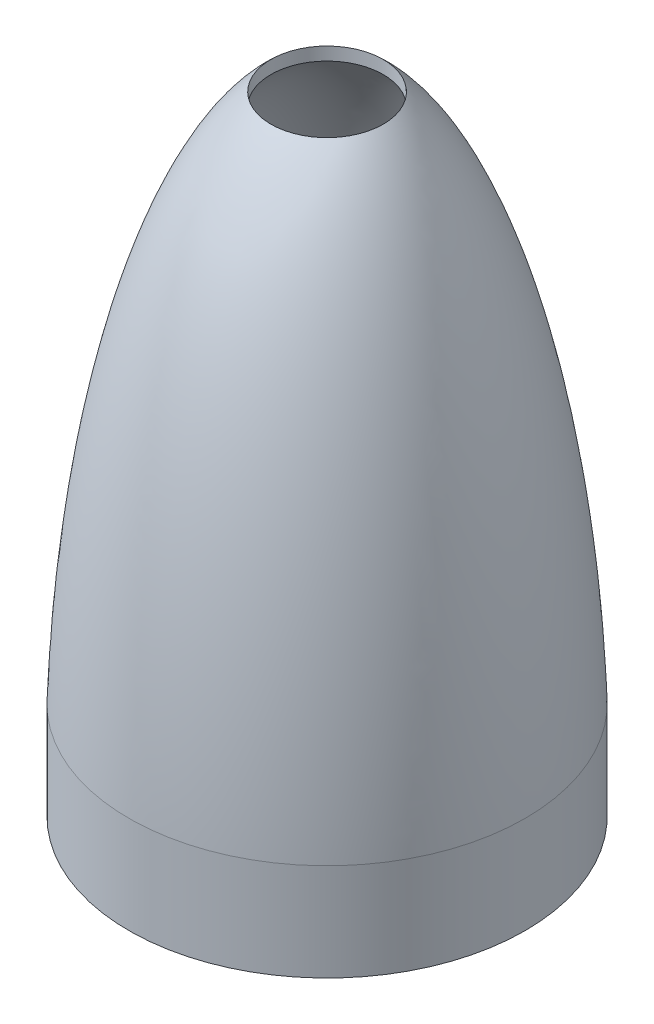
SolidWorks part; units mm, degrees
material "VeroWhite Plus"
ref_plane "Front Plane" through (0, 0, 0) normal (0, 0, 1) x (1, 0, 0)
ref_plane "Top Plane" through (0, 0, 0) normal (0, 1, 0) x (1, 0, 0)
ref_plane "Right Plane" through (0, 0, 0) normal (1, 0, 0) x (0, 0, -1)
sketch "Sketch1" plane through (0, 0, 0) normal (0, 0, 1) x (1, 0, 0)
  line L0 (0, 0) -> (57.6864, 0) construction
  line L1 (0, 19.918) -> (0, 197.9164) construction
  line L2 (0, 19.918) -> (63.5, 19.918) construction
  line L3 (0, 19.918) -> (0, 0) construction
  line L13 (0, 197.9164) -> (0, 194.918)
  line L14 (63.5, 19.918) -> (63.5, -11.258)
  line L15 (63.5, -11.258) -> (60.5, -11.258)
  line L16 (60.5, -11.258) -> (60.5, 19.918)
  ellipse E1 centre (0, 0) end of major axis (0, 197.9164) minor radius 63.824 (63.5, 19.918) -> (0, 197.9164) ccw
  spline S0 degree 1 poles (60.5032, 19.8202) (0, 194.918) knots 0 0 1 1 construction
  spline S1 degree 3 poles (60.5032, 19.8202) (60.5024, 19.8446) (60.5011, 19.8854) (60.4027, 22.885) (60.1628, 28.8505) (59.5081, 40.6956) (58.3579, 55.3596) (56.4637, 72.479) (53.2754, 94.4792) (48.0987, 120.0698) (40.2045, 146.6573) (30.9343, 168.1839) (22.3996, 181.2376) (15.3903, 188.4638) (10.1461, 192.2524) (5.8682, 194.0812) (2.5035, 194.7993) (0.838, 194.918) (0, 194.918) knots -1.469987 -1.469987 -1.469987 -1.469987 -1.469613 -1.469364 -1.42405 -1.378113 -1.286239 -1.194365 -1.10249 -0.918742 -0.734994 -0.551245 -0.367497 -0.275623 -0.183748 -0.091874 -0.045937 0 0 0 0 only from (60.5, 19.918) to (0, 194.918)
  dimension "D1" = 63.5
  dimension "D2" = 31.176
  dimension "D3" = 19.918
  dimension "D4" = 3
  dimension "D5" = 175
revolve "Revolve1" add sketch "Sketch1" angle 360 about L1
ref_plane "Plane1" through (0, -11.258, 0) normal (0, -1, 0) x (-1, 0, 0)
sketch "Sketch3" plane through (0, 0, 0) normal (0, 1, 0) x (1, 0, 0)
  circle A0 centre (0, 0) radius 1.125
  dimension "D1" = 2.25
extrude "Cut-Extrude2" cut sketch "Sketch3" along normal up to next
fillet "Fillet1" radius 2 1 edges at (1.125, 197.8856, 0)
ref_plane "Plane2" through (0, 197.6259, 0) normal (0, -1, 0) x (-1, 0, 0)
sketch "Sketch4" plane through (0, -11.258, 0) normal (0, -1, 0) x (-1, 0, 0)
  circle A0 centre (0, 0) radius 18
  dimension "D1" = 36
extrude "Cut-Extrude3" cut sketch "Sketch4" against normal up to next
